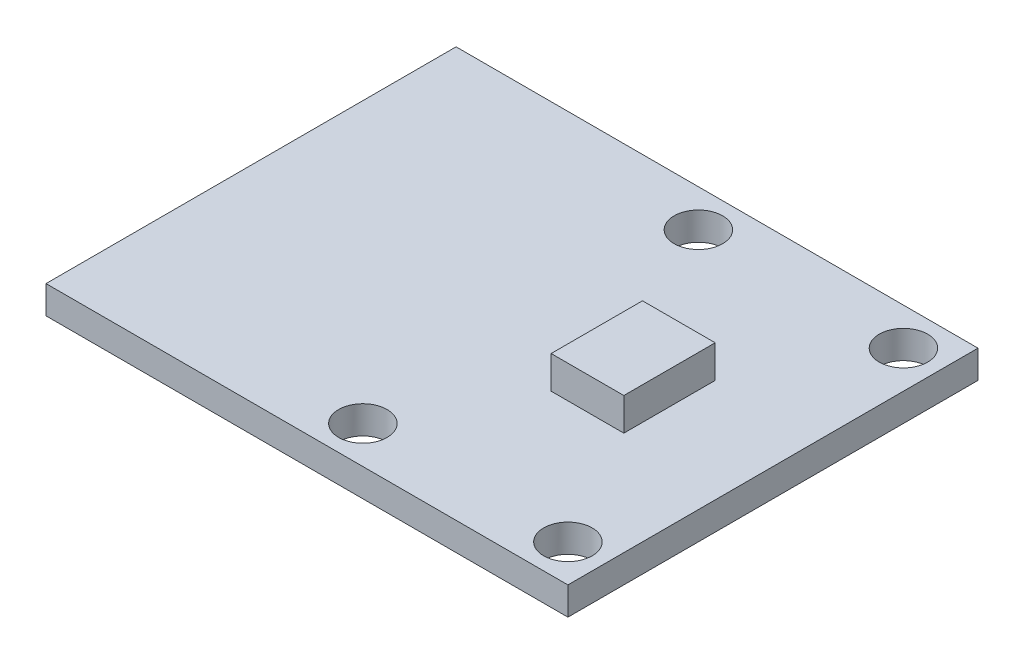
SolidWorks part; units mm, degrees
ref_plane "Front Plane" through (0, 0, 0) normal (0, 0, 1) x (1, 0, 0)
ref_plane "Top Plane" through (0, 0, 0) normal (0, 1, 0) x (1, 0, 0)
ref_plane "Right Plane" through (0, 0, 0) normal (1, 0, 0) x (0, 0, -1)
sketch "Sketch1" plane through (0, 0, 0) normal (0, 1, 0) x (1, 0, 0)
  line L1 (-14, -11) -> (14, -11)
  line L2 (-14, -11) -> (-14, 11)
  line L3 (-14, 11) -> (14, 11)
  line L4 (14, -11) -> (14, 11)
  line L5 (-14, -11) -> (14, 11) construction
  line L6 (-14, 11) -> (14, -11) construction
  point P0 (0, 0)
  dimension "D1" = 28
  dimension "D2" = 22
extrude "Boss-Extrude1" add sketch "Sketch1" along normal blind 1.5
sketch "Sketch2" plane through (0, 1.5, 0) normal (0, 1, 0) x (1, 0, 0)
  line L0 (-55, 0) -> (55, 0) construction
  line L1 (4.55, -2.45) -> (8.45, -2.45)
  line L2 (4.55, -2.45) -> (4.55, 2.45)
  line L3 (4.55, 2.45) -> (8.45, 2.45)
  line L4 (8.45, -2.45) -> (8.45, 2.45)
  line L5 (4.55, -2.45) -> (8.45, 2.45) construction
  line L6 (4.55, 2.45) -> (8.45, -2.45) construction
  line L7 (6.5, -2.45) -> (6.5, 2.45) construction
  line L8 (14, -11) -> (14, 11) construction
  point P0 (6.5, 0)
  dimension "D1" = 7.5
  dimension "D2" = 4.9
  dimension "D3" = 3.9
extrude "Boss-Extrude2" add sketch "Sketch2" along normal blind 1.75
sketch "Sketch3" plane through (0, 1.5, 0) normal (0, 1, 0) x (1, 0, 0)
  line L0 (-1.7875, 0) -> (1.7875, 0) construction
  line L2 (14, -11) -> (14, 11) construction
  circle A0 centre (12, -9) radius 1.3
  circle A1 centre (1, -9) radius 1.3
  circle A2 centre (12, 9) radius 1.3
  circle A3 centre (1, 9) radius 1.3
  dimension "D1" = 2.6
  dimension "D2" = 11
  dimension "D3" = 18
  dimension "D4" = 2
extrude "Cut-Extrude1" cut sketch "Sketch3" against normal blind 1.75
